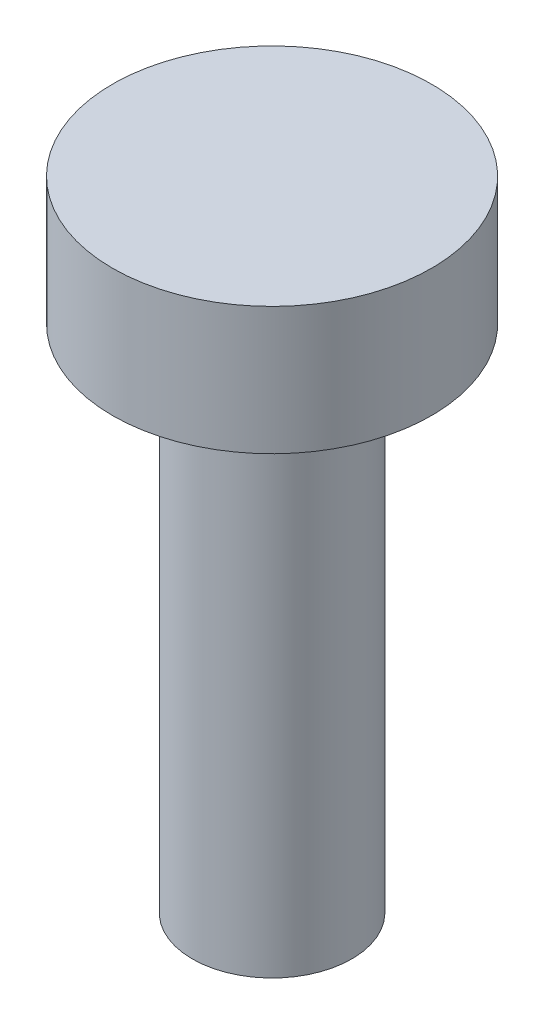
SolidWorks part; units mm, degrees
material "1023 Carbon Steel Sheet (SS)"
ref_plane "Front Plane" through (0, 0, 0) normal (0, 0, 1) x (1, 0, 0)
ref_plane "Top Plane" through (0, 0, 0) normal (0, 1, 0) x (1, 0, 0)
ref_plane "Right Plane" through (0, 0, 0) normal (1, 0, 0) x (0, 0, -1)
sketch "Sketch1" plane through (0, 0, 0) normal (0, 0, 1) x (1, 0, 0)
  line L0 (0, 0) -> (1.25, 0)
  line L1 (55, 0) -> (-55, 0) construction
  line L2 (1.25, 0) -> (1.25, 8)
  line L3 (1.25, 8) -> (2.5, 8)
  line L4 (2.5, 8) -> (2.5, 10)
  line L5 (2.5, 10) -> (0, 10)
  line L6 (0, -55) -> (0, 55) construction
  line L7 (0, 10) -> (0, 0)
  dimension "D1" = 10
  dimension "D2" = 8
  dimension "D3" = 1.25
  dimension "D4" = 2.5
revolve "Revolve1" add sketch "Sketch1" angle 360 about L7
